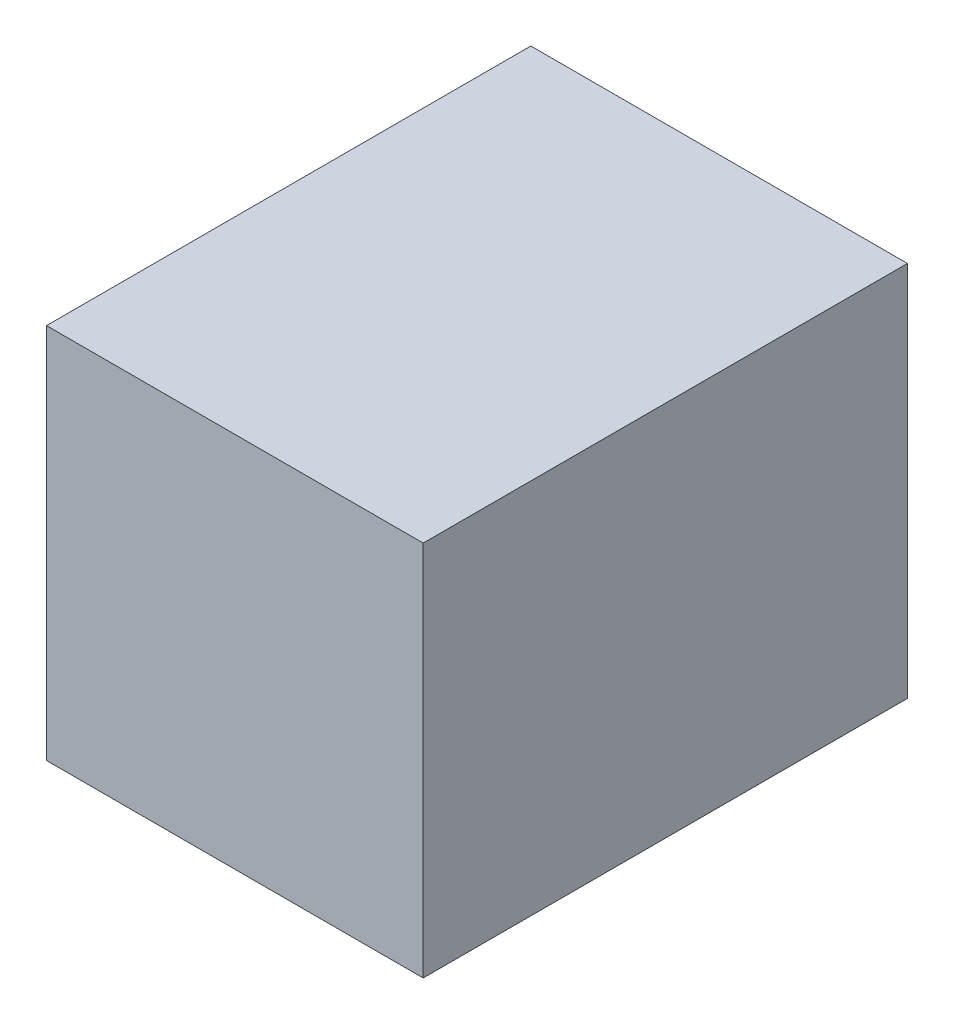
SolidWorks part; units mm, degrees
ref_plane "Plan de face" through (0, 0, 0) normal (0, 0, 1) x (1, 0, 0)
ref_plane "Plan de dessus" through (0, 0, 0) normal (0, 1, 0) x (1, 0, 0)
ref_plane "Plan de droite" through (0, 0, 0) normal (1, 0, 0) x (0, 0, -1)
sketch "Esquisse1" plane through (0, 0, 0) normal (0, 0, 1) x (1, 0, 0)
  line L1 (0, 0) -> (350, 0)
  line L2 (0, 0) -> (0, 350)
  line L3 (0, 350) -> (350, 350)
  line L4 (350, 0) -> (350, 350)
  dimension "D1" = 350
  dimension "D2" = 350
extrude "Boss.-Extru.1" add sketch "Esquisse1" along normal blind 450
